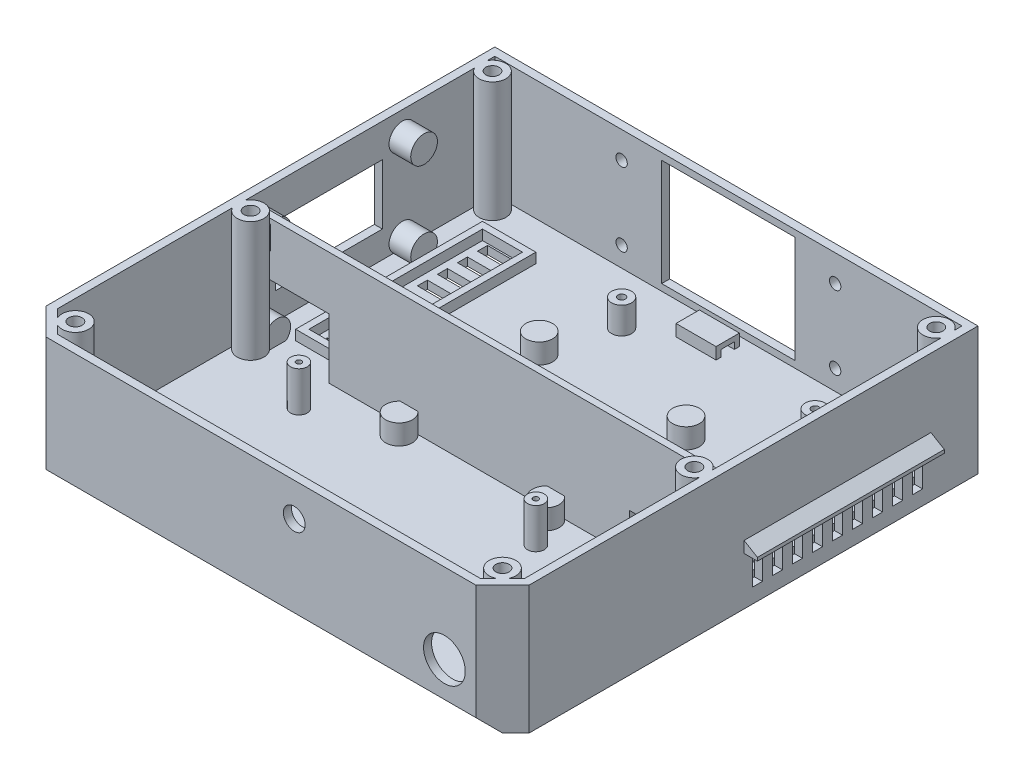
SolidWorks part; units mm, degrees
ref_plane "Front Plane" through (0, 0, 0) normal (0, 0, 1) x (1, 0, 0)
ref_plane "Top Plane" through (0, 0, 0) normal (0, 1, 0) x (1, 0, 0)
ref_plane "Right Plane" through (0, 0, 0) normal (1, 0, 0) x (0, 0, -1)
ref_plane "PZm28_4" through (0, -28.4, 0) normal (0, 1, 0) x (1, 0, 0)
sketch "Sketch1" plane through (0, -28.4, 0) normal (0, 1, 0) x (1, 0, 0)
  line L0 (-64.4, -154.4) -> (64.4, -154.4)
  line L1 (64.4, -154.4) -> (72.4, -146.4)
  line L2 (72.4, -146.4) -> (72.4, -11.9)
  line L3 (72.4, -11.9) -> (-72.4, -11.9)
  line L4 (-72.4, -11.9) -> (-72.4, -146.4)
  line L5 (-72.4, -146.4) -> (-64.4, -154.4)
extrude "Box Block" add sketch "Sketch1" along normal blind 38.4
sketch "Sketch2" plane through (0, 0, 0) normal (1, 0, 0) x (0, 0, -1)
  line L0 (-155.4, -23.4) -> (-149.4, -29.4)
  line L1 (-149.4, -29.4) -> (-155.4, -29.4)
  line L2 (-155.4, -29.4) -> (-155.4, -23.4)
extrude "Rear Bottom Facet" cut sketch "Sketch2" against normal through all and the other way through all
shell "Shell" thickness 2.4
ref_plane "PZm26_5" through (0, -26.5, 0) normal (0, 1, 0) x (1, 0, 0)
sketch "Sketch3" plane through (0, -26.5, 0) normal (0, 1, 0) x (1, 0, 0)
  line L0 (-70.1, -88) -> (70.1, -88)
  line L1 (70.1, -88) -> (70.1, -86)
  line L2 (70.1, -86) -> (-70.1, -86)
  line L3 (-70.1, -86) -> (-70.1, -88)
extrude "Divider" add sketch "Sketch3" along normal blind 34.5
ref_plane "PY85_5" through (0, 0, 85.5) normal (0, 0, 1) x (1, 0, 0)
sketch "Sketch4" plane through (0, 0, 85.5) normal (0, 0, 1) x (1, 0, 0)
  line L0 (-70.5, -26) -> (-46, -26)
  line L1 (-46, -26) -> (-46, -8)
  line L2 (-46, -8) -> (-70.5, -8)
  line L3 (-70.5, -8) -> (-70.5, -26)
  line L4 (44, -26) -> (70.5, -26)
  line L5 (70.5, -26) -> (70.5, -14)
  line L6 (70.5, -14) -> (44, -14)
  line L7 (44, -14) -> (44, -26)
extrude "Divider Lead Notches" cut sketch "Sketch4" along normal blind 3
ref_plane "PY11_4" through (0, 0, 11.4) normal (0, 0, 1) x (1, 0, 0)
sketch "Sketch5" plane through (0, 0, 11.4) normal (0, 0, 1) x (1, 0, 0)
  line L0 (-20, -24) -> (20, -24)
  line L1 (20, -24) -> (20, 8)
  line L2 (20, 8) -> (-20, 8)
  line L3 (-20, 8) -> (-20, -24)
  circle A0 centre (-32, 2) radius 1.7
  circle A1 centre (32, 2) radius 1.7
  circle A2 centre (-32, -20) radius 1.7
  circle A3 centre (32, -20) radius 1.7
extrude "Cable Window and Flange Holes" cut sketch "Sketch5" along normal blind 3.4
sketch "Sketch6" plane through (0, -26.5, 0) normal (0, 1, 0) x (1, 0, 0)
  circle A0 centre (41.5, -29.8) radius 3
  circle A1 centre (-16.5, -29.8) radius 3
  circle A2 centre (41.5, -78.8) radius 3
  circle A3 centre (-16.5, -78.8) radius 3
extrude "Pi Standoffs" add sketch "Sketch6" along normal blind 8.5
ref_plane "PZm25" through (0, -25, 0) normal (0, 1, 0) x (1, 0, 0)
sketch "Sketch7" plane through (0, -25, 0) normal (0, 1, 0) x (1, 0, 0)
  circle A0 centre (41.5, -29.8) radius 1.1
  circle A1 centre (-16.5, -29.8) radius 1.1
  circle A2 centre (41.5, -78.8) radius 1.1
  circle A3 centre (-16.5, -78.8) radius 1.1
extrude "Pi Pilots" cut sketch "Sketch7" along normal blind 7.5
sketch "Sketch8" plane through (0, -26.5, 0) normal (0, 1, 0) x (1, 0, 0)
  circle A0 centre (-44, -147) radius 2.5
  circle A1 centre (-44, -99) radius 2.5
  circle A2 centre (27, -147) radius 2.5
  circle A3 centre (27, -99) radius 2.5
extrude "ESP32 Standoffs" add sketch "Sketch8" along normal blind 12.5
sketch "Sketch9" plane through (0, -25, 0) normal (0, 1, 0) x (1, 0, 0)
  circle A0 centre (-44, -147) radius 0.8
  circle A1 centre (-44, -99) radius 0.8
  circle A2 centre (27, -147) radius 0.8
  circle A3 centre (27, -99) radius 0.8
extrude "ESP32 Pilots" cut sketch "Sketch9" along normal blind 11.5
sketch "Sketch10" plane through (0, -26.5, 0) normal (0, 1, 0) x (1, 0, 0)
  circle A0 centre (-66.5, -18.5) radius 4
extrude "Lid Boss 1" add sketch "Sketch10" along normal blind 36.5
sketch "Sketch11" plane through (0, -26.5, 0) normal (0, 1, 0) x (1, 0, 0)
  circle A0 centre (66.5, -18.5) radius 4
extrude "Lid Boss 2" add sketch "Sketch11" along normal blind 36.5
sketch "Sketch12" plane through (0, -26.5, 0) normal (0, 1, 0) x (1, 0, 0)
  circle A0 centre (-66.5, -91) radius 4
extrude "Lid Boss 3" add sketch "Sketch12" along normal blind 36.5
sketch "Sketch13" plane through (0, -26.5, 0) normal (0, 1, 0) x (1, 0, 0)
  circle A0 centre (66.5, -91) radius 4
extrude "Lid Boss 4" add sketch "Sketch13" along normal blind 36.5
sketch "Sketch14" plane through (0, -26.5, 0) normal (0, 1, 0) x (1, 0, 0)
  circle A0 centre (-64, -146) radius 4
extrude "Lid Boss 5" add sketch "Sketch14" along normal blind 36.5
sketch "Sketch15" plane through (0, -26.5, 0) normal (0, 1, 0) x (1, 0, 0)
  circle A0 centre (64, -146) radius 4
extrude "Lid Boss 6" add sketch "Sketch15" along normal blind 36.5
ref_plane "PZ4" through (0, 4, 0) normal (0, 1, 0) x (1, 0, 0)
sketch "Sketch16" plane through (0, 4, 0) normal (0, 1, 0) x (1, 0, 0)
  circle A0 centre (-66.5, -18.5) radius 2
  circle A1 centre (66.5, -18.5) radius 2
  circle A2 centre (-66.5, -91) radius 2
  circle A3 centre (66.5, -91) radius 2
  circle A4 centre (-64, -146) radius 2
  circle A5 centre (64, -146) radius 2
extrude "Lid Insert Holes" cut sketch "Sketch16" along normal blind 6.5
sketch "Sketch17" plane through (0, -26.5, 0) normal (0, 1, 0) x (1, 0, 0)
  line L0 (47, -82) -> (69, -82)
  line L1 (69, -82) -> (69, -26)
  line L2 (69, -26) -> (47, -26)
  line L3 (47, -26) -> (47, -82)
  line L4 (49, -80) -> (67, -80)
  line L5 (67, -80) -> (67, -28)
  line L6 (67, -28) -> (49, -28)
  line L7 (49, -28) -> (49, -80)
extrude "Intake Upstand" add sketch "Sketch17" along normal blind 3.5
ref_plane "PZm29_4" through (0, -29.4, 0) normal (0, 1, 0) x (1, 0, 0)
sketch "Sketch18" plane through (0, -29.4, 0) normal (0, 1, 0) x (1, 0, 0)
  line L0 (51, -31.5) -> (65, -31.5)
  line L1 (65, -31.5) -> (65, -28.5)
  line L2 (65, -28.5) -> (51, -28.5)
  line L3 (51, -28.5) -> (51, -31.5)
  line L4 (51, -37.5) -> (65, -37.5)
  line L5 (65, -37.5) -> (65, -34.5)
  line L6 (65, -34.5) -> (51, -34.5)
  line L7 (51, -34.5) -> (51, -37.5)
  line L8 (51, -43.5) -> (65, -43.5)
  line L9 (65, -43.5) -> (65, -40.5)
  line L10 (65, -40.5) -> (51, -40.5)
  line L11 (51, -40.5) -> (51, -43.5)
  line L12 (51, -49.5) -> (65, -49.5)
  line L13 (65, -49.5) -> (65, -46.5)
  line L14 (65, -46.5) -> (51, -46.5)
  line L15 (51, -46.5) -> (51, -49.5)
  line L16 (51, -55.5) -> (65, -55.5)
  line L17 (65, -55.5) -> (65, -52.5)
  line L18 (65, -52.5) -> (51, -52.5)
  line L19 (51, -52.5) -> (51, -55.5)
  line L20 (51, -61.5) -> (65, -61.5)
  line L21 (65, -61.5) -> (65, -58.5)
  line L22 (65, -58.5) -> (51, -58.5)
  line L23 (51, -58.5) -> (51, -61.5)
  line L24 (51, -67.5) -> (65, -67.5)
  line L25 (65, -67.5) -> (65, -64.5)
  line L26 (65, -64.5) -> (51, -64.5)
  line L27 (51, -64.5) -> (51, -67.5)
  line L28 (51, -73.5) -> (65, -73.5)
  line L29 (65, -73.5) -> (65, -70.5)
  line L30 (65, -70.5) -> (51, -70.5)
  line L31 (51, -70.5) -> (51, -73.5)
  line L32 (51, -79.5) -> (65, -79.5)
  line L33 (65, -79.5) -> (65, -76.5)
  line L34 (65, -76.5) -> (51, -76.5)
  line L35 (51, -76.5) -> (51, -79.5)
extrude "Intake Slots" cut sketch "Sketch18" along normal blind 3.9
sketch "Sketch19" plane through (0, -26.5, 0) normal (0, 1, 0) x (1, 0, 0)
  line L0 (-62, -82) -> (-46, -82)
  line L1 (-46, -82) -> (-46, -26)
  line L2 (-46, -26) -> (-62, -26)
  line L3 (-62, -26) -> (-62, -82)
  line L4 (-60, -80) -> (-48, -80)
  line L5 (-48, -80) -> (-48, -28)
  line L6 (-48, -28) -> (-60, -28)
  line L7 (-60, -28) -> (-60, -80)
extrude "Exhaust Upstand" add sketch "Sketch19" along normal blind 3.5
sketch "Sketch20" plane through (0, -29.4, 0) normal (0, 1, 0) x (1, 0, 0)
  line L0 (-58, -31.5) -> (-50, -31.5)
  line L1 (-50, -31.5) -> (-50, -28.5)
  line L2 (-50, -28.5) -> (-58, -28.5)
  line L3 (-58, -28.5) -> (-58, -31.5)
  line L4 (-58, -37.5) -> (-50, -37.5)
  line L5 (-50, -37.5) -> (-50, -34.5)
  line L6 (-50, -34.5) -> (-58, -34.5)
  line L7 (-58, -34.5) -> (-58, -37.5)
  line L8 (-58, -43.5) -> (-50, -43.5)
  line L9 (-50, -43.5) -> (-50, -40.5)
  line L10 (-50, -40.5) -> (-58, -40.5)
  line L11 (-58, -40.5) -> (-58, -43.5)
  line L12 (-58, -49.5) -> (-50, -49.5)
  line L13 (-50, -49.5) -> (-50, -46.5)
  line L14 (-50, -46.5) -> (-58, -46.5)
  line L15 (-58, -46.5) -> (-58, -49.5)
  line L16 (-58, -55.5) -> (-50, -55.5)
  line L17 (-50, -55.5) -> (-50, -52.5)
  line L18 (-50, -52.5) -> (-58, -52.5)
  line L19 (-58, -52.5) -> (-58, -55.5)
  line L20 (-58, -61.5) -> (-50, -61.5)
  line L21 (-50, -61.5) -> (-50, -58.5)
  line L22 (-50, -58.5) -> (-58, -58.5)
  line L23 (-58, -58.5) -> (-58, -61.5)
  line L24 (-58, -67.5) -> (-50, -67.5)
  line L25 (-50, -67.5) -> (-50, -64.5)
  line L26 (-50, -64.5) -> (-58, -64.5)
  line L27 (-58, -64.5) -> (-58, -67.5)
  line L28 (-58, -73.5) -> (-50, -73.5)
  line L29 (-50, -73.5) -> (-50, -70.5)
  line L30 (-50, -70.5) -> (-58, -70.5)
  line L31 (-58, -70.5) -> (-58, -73.5)
  line L32 (-58, -79.5) -> (-50, -79.5)
  line L33 (-50, -79.5) -> (-50, -76.5)
  line L34 (-50, -76.5) -> (-58, -76.5)
  line L35 (-58, -76.5) -> (-58, -79.5)
extrude "Exhaust Slots" cut sketch "Sketch20" along normal blind 3.9
ref_plane "PX69_5" through (69.5, 0, 0) normal (1, 0, 0) x (0, 0, -1)
sketch "Sketch21" plane through (69.5, 0, 0) normal (1, 0, 0) x (0, 0, -1)
  line L0 (-31.5, -24) -> (-28.5, -24)
  line L1 (-28.5, -24) -> (-28.5, -16)
  line L2 (-28.5, -16) -> (-31.5, -16)
  line L3 (-31.5, -16) -> (-31.5, -24)
  line L4 (-37.5, -24) -> (-34.5, -24)
  line L5 (-34.5, -24) -> (-34.5, -16)
  line L6 (-34.5, -16) -> (-37.5, -16)
  line L7 (-37.5, -16) -> (-37.5, -24)
  line L8 (-43.5, -24) -> (-40.5, -24)
  line L9 (-40.5, -24) -> (-40.5, -16)
  line L10 (-40.5, -16) -> (-43.5, -16)
  line L11 (-43.5, -16) -> (-43.5, -24)
  line L12 (-49.5, -24) -> (-46.5, -24)
  line L13 (-46.5, -24) -> (-46.5, -16)
  line L14 (-46.5, -16) -> (-49.5, -16)
  line L15 (-49.5, -16) -> (-49.5, -24)
  line L16 (-55.5, -24) -> (-52.5, -24)
  line L17 (-52.5, -24) -> (-52.5, -16)
  line L18 (-52.5, -16) -> (-55.5, -16)
  line L19 (-55.5, -16) -> (-55.5, -24)
  line L20 (-61.5, -24) -> (-58.5, -24)
  line L21 (-58.5, -24) -> (-58.5, -16)
  line L22 (-58.5, -16) -> (-61.5, -16)
  line L23 (-61.5, -16) -> (-61.5, -24)
  line L24 (-67.5, -24) -> (-64.5, -24)
  line L25 (-64.5, -24) -> (-64.5, -16)
  line L26 (-64.5, -16) -> (-67.5, -16)
  line L27 (-67.5, -16) -> (-67.5, -24)
  line L28 (-73.5, -24) -> (-70.5, -24)
  line L29 (-70.5, -24) -> (-70.5, -16)
  line L30 (-70.5, -16) -> (-73.5, -16)
  line L31 (-73.5, -16) -> (-73.5, -24)
  line L32 (-79.5, -24) -> (-76.5, -24)
  line L33 (-76.5, -24) -> (-76.5, -16)
  line L34 (-76.5, -16) -> (-79.5, -16)
  line L35 (-79.5, -16) -> (-79.5, -24)
extrude "Side Vents" cut sketch "Sketch21" along normal blind 3.4
ref_plane "PY26" through (0, 0, 26) normal (0, 0, 1) x (1, 0, 0)
sketch "Sketch22" plane through (0, 0, 26) normal (0, 0, 1) x (1, 0, 0)
  line L0 (72.2, -14) -> (76.4, -14)
  line L1 (76.4, -14) -> (76.4, -13)
  line L2 (76.4, -13) -> (72.2, -10.5)
  line L3 (72.2, -10.5) -> (72.2, -14)
extrude "Side Vent Drip Ledge" add sketch "Sketch22" along normal blind 56
ref_plane "PXm72_9" through (-72.9, 0, 0) normal (1, 0, 0) x (0, 0, -1)
sketch "Sketch23" plane through (-72.9, 0, 0) normal (1, 0, 0) x (0, 0, -1)
  line L0 (-80, -18) -> (-48, -18)
  line L1 (-48, -18) -> (-48, 0)
  line L2 (-48, 0) -> (-80, 0)
  line L3 (-80, 0) -> (-80, -18)
extrude "USB Hatch Opening" cut sketch "Sketch23" along normal blind 3.4
ref_plane "PXm70_1" through (-70.1, 0, 0) normal (1, 0, 0) x (0, 0, -1)
sketch "Sketch24" plane through (-70.1, 0, 0) normal (1, 0, 0) x (0, 0, -1)
  circle A0 centre (-86, -23) radius 4
  circle A1 centre (-86, 3) radius 4
  circle A2 centre (-42, -23) radius 4
  circle A3 centre (-42, 3) radius 4
extrude "Hatch Bosses" add sketch "Sketch24" along normal blind 6.6
sketch "Sketch25" plane through (-72.9, 0, 0) normal (1, 0, 0) x (0, 0, -1)
  circle A0 centre (-86, -23) radius 2
  circle A1 centre (-86, 3) radius 2
  circle A2 centre (-42, -23) radius 2
  circle A3 centre (-42, 3) radius 2
extrude "Hatch Insert Holes" cut sketch "Sketch25" along normal blind 7
ref_plane "PY151_5" through (0, 0, 151.5) normal (0, 0, 1) x (1, 0, 0)
sketch "Sketch26" plane through (0, 0, 151.5) normal (0, 0, 1) x (1, 0, 0)
  circle A0 centre (10, 0) radius 3.25
  circle A1 centre (55, -14) radius 6.25
extrude "SMA and Gland Holes" cut sketch "Sketch26" along normal blind 3.4
sketch "Sketch27" plane through (0, -26.5, 0) normal (0, 1, 0) x (1, 0, 0)
  line L0 (-6, -24) -> (6, -24)
  line L1 (6, -24) -> (6, -17)
  line L2 (6, -17) -> (-6, -17)
  line L3 (-6, -17) -> (-6, -24)
extrude "Bundle Tie Anchor" add sketch "Sketch27" along normal blind 4
ref_plane "PXm7" through (-7, 0, 0) normal (1, 0, 0) x (0, 0, -1)
sketch "Sketch28" plane through (-7, 0, 0) normal (1, 0, 0) x (0, 0, -1)
  line L0 (-22.5, -26) -> (-18.5, -26)
  line L1 (-18.5, -26) -> (-18.5, -24)
  line L2 (-18.5, -24) -> (-22.5, -24)
  line L3 (-22.5, -24) -> (-22.5, -26)
extrude "Bundle Tie Slot" cut sketch "Sketch28" along normal blind 14
sketch "Sketch29" plane through (0, -26.5, 0) normal (0, 1, 0) x (1, 0, 0)
  line L0 (41, -134.5) -> (51, -134.5)
  line L1 (51, -134.5) -> (51, -127.5)
  line L2 (51, -127.5) -> (41, -127.5)
  line L3 (41, -127.5) -> (41, -134.5)
extrude "Buck Tie Anchor 1" add sketch "Sketch29" along normal blind 4
ref_plane "PX40" through (40, 0, 0) normal (1, 0, 0) x (0, 0, -1)
sketch "Sketch30" plane through (40, 0, 0) normal (1, 0, 0) x (0, 0, -1)
  line L0 (-133, -26) -> (-129, -26)
  line L1 (-129, -26) -> (-129, -24)
  line L2 (-129, -24) -> (-133, -24)
  line L3 (-133, -24) -> (-133, -26)
extrude "Buck Tie Slot 1" cut sketch "Sketch30" along normal blind 12
sketch "Sketch31" plane through (0, -26.5, 0) normal (0, 1, 0) x (1, 0, 0)
  line L0 (41, -104.5) -> (51, -104.5)
  line L1 (51, -104.5) -> (51, -97.5)
  line L2 (51, -97.5) -> (41, -97.5)
  line L3 (41, -97.5) -> (41, -104.5)
extrude "Buck Tie Anchor 2" add sketch "Sketch31" along normal blind 4
sketch "Sketch32" plane through (40, 0, 0) normal (1, 0, 0) x (0, 0, -1)
  line L0 (-103, -26) -> (-99, -26)
  line L1 (-99, -26) -> (-99, -24)
  line L2 (-99, -24) -> (-103, -24)
  line L3 (-103, -24) -> (-103, -26)
extrude "Buck Tie Slot 2" cut sketch "Sketch32" along normal blind 12
sketch "Sketch33" plane through (0, -26.5, 0) normal (0, 1, 0) x (1, 0, 0)
  circle A0 centre (-22, -91) radius 4
  circle A1 centre (-22, -49) radius 4
  circle A2 centre (22, -91) radius 4
  circle A3 centre (22, -49) radius 4
extrude "Rail Plate Bosses" add sketch "Sketch33" along normal blind 6.5
ref_plane "PZm28_9" through (0, -28.9, 0) normal (0, 1, 0) x (1, 0, 0)
sketch "Sketch34" plane through (0, -28.9, 0) normal (0, 1, 0) x (1, 0, 0)
  circle A0 centre (-22, -91) radius 2
  circle A1 centre (-22, -49) radius 2
  circle A2 centre (22, -91) radius 2
  circle A3 centre (22, -49) radius 2
extrude "Rail Insert Holes" cut sketch "Sketch34" along normal blind 6.5
equation "\"BOARD_REAR\" = 86.0"
equation "\"BOARD_FRONT\" = 41.0"
equation "\"BOARD_END\" = 22.0"
equation "\"BOARD_ANGLED\" = 30.0"
equation "\"BOARD_DEPTH\" = 41.8431"
equation "\"PCB_T\" = 1.6"
equation "\"ABOVE_PCB\" = 14.0"
equation "\"BELOW_PCB\" = 6.0"
equation "\"MID_PARTS_H\" = 9.0"
equation "\"BOARD_HOLE_PILOT\" = 1.6"
equation "\"J2_X\" = 19.0"
equation "\"DUPONT_DROP\" = 14.0"
equation "\"BEND_R\" = 5.0"
equation "\"BOARD_GAP\" = 3.0"
equation "\"TOF_FOV\" = 25.0"
equation "\"TOF_MARGIN_DEG\" = 5.0"
equation "\"TOF_WIN_MARGIN\" = 1.0"
equation "\"TOF_Z\" = 9.0"
equation "\"TOF_SIDE_BEARING\" = 90.0"
equation "\"TOF_CONE_LEN\" = 70.0"
equation "\"CAM_W\" = 29.2"
equation "\"CAM_H\" = 28.2"
equation "\"CAM_D\" = 12.35"
equation "\"CAM_FRONT_Y\" = 43.0"
equation "\"CAM_BOTTOM_Z\" = 17.0"
equation "\"CAM_LENS_UP\" = 11.6"
equation "\"CAM_LENS_OPEN\" = 9.6"
equation "\"CAM_HFOV\" = 53.5"
equation "\"CAM_VFOV\" = 41.41"
equation "\"CAM_FOV_MARGIN\" = 3.0"
equation "\"CAM_FIT\" = 0.3"
equation "\"RIBBON_W\" = 16.0"
equation "\"RIBBON_T\" = 0.3"
equation "\"RIBBON_LEN\" = 150.0"
equation "\"RIBBON_EXIT_Y\" = 35.0"
equation "\"WALL\" = 2.4"
equation "\"HEAD_X\" = 48.4"
equation "\"HEAD_REAR_Y\" = -11.9"
equation "\"CAM_FOAM\" = 2.8"
equation "\"HEAD_FRONT_Y\" = 48.2"
equation "\"HEAD_TOP_Z\" = 50.6"
equation "\"HEAD_BOT_Z\" = -28.4"
equation "\"HEAD_SPLIT_Z\" = -4.0"
equation "\"SKIRT_T\" = 1.2"
equation "\"SKIRT_H\" = 3.0"
equation "\"SKIRT_FIT\" = 0.3"
equation "\"VISOR\" = 7.8"
equation "\"VISOR_Z\" = 40.0"
equation "\"ROOF_SLOPE_Y\" = 40.0"
equation "\"ROOF_CHAMFER\" = 10.0"
equation "\"REAR_CHAMFER\" = 10.0"
equation "\"CORNER_CHAMFER\" = 6.0"
equation "\"LOWER_SIDE_FACET\" = 6.0"
equation "\"LIGHTBAR_DEPTH\" = 1.0"
equation "\"HOOD_Z\" = 14.0"
equation "\"HOOD_L\" = 6.0"
equation "\"SIDE_HOOD_L\" = 4.0"
equation "\"INSERT_M3_D\" = 4.0"
equation "\"INSERT_M3_L\" = 6.0"
equation "\"M3_CLEAR\" = 3.4"
equation "\"M2_PILOT\" = 1.6"
equation "\"M25_PILOT\" = 2.2"
equation "\"BOX_X\" = 72.4"
equation "\"BOX_FRONT_Y\" = -11.9"
equation "\"BOX_REAR_Y\" = -154.4"
equation "\"BOX_BOT_Z\" = -28.4"
equation "\"BOX_TOP_Z\" = 10.0"
equation "\"LID_T\" = 2.4"
equation "\"LID_SKIRT\" = 1.6"
equation "\"LID_TONGUE_H\" = 3.0"
equation "\"LID_FIT\" = 0.3"
equation "\"GNSS_WIN_T\" = 1.2"
equation "\"DIVIDER_Y\" = -86.0"
equation "\"PI_X0\" = -40.0"
equation "\"PI_X1\" = 45.0"
equation "\"PI_Y1\" = -26.3"
equation "\"PI_Y0\" = -82.3"
equation "\"PI_STANDOFF\" = 8.0"
equation "\"ESP_X0\" = -46.0"
equation "\"ESP_Y0\" = -149.0"
equation "\"ESP_L\" = 75.0"
equation "\"ESP_W\" = 52.0"
equation "\"ESP_STANDOFF\" = 12.0"
equation "\"BOX_REAR_CHAMFER\" = 8.0"
equation "\"BOX_REAR_FACET\" = 4.0"
equation "\"VENT_UPSTAND\" = 3.0"
equation "\"TUBE_D\" = 22.2"
equation "\"TUBE_LINER\" = 1.0"
equation "\"MOUNT_Y\" = -70.0"
equation "\"RAIL_W\" = 30.0"
equation "\"RAIL_W2\" = 38.0"
equation "\"RAIL_H\" = 6.0"
equation "\"SLIDE\" = 0.3"
equation "\"STOP_T\" = 6.0"
equation "\"CLAMP_W\" = 40.0"
equation "\"CLAMP_HALF\" = 20.0"
equation "\"CLAMP_DROP\" = 12.0"
equation "\"CAP_T\" = 12.0"
equation "\"CLAMP_BOLT_OFF\" = 16.6"
equation "\"M5_INSERT_D\" = 6.4"
equation "\"M5_CLEAR\" = 5.5"
equation "\"LOCK_D\" = 3.3"
equation "\"POD_TILT_DEG\" = 0.0"
equation "\"PRINT_LIMIT\" = 180.0"
